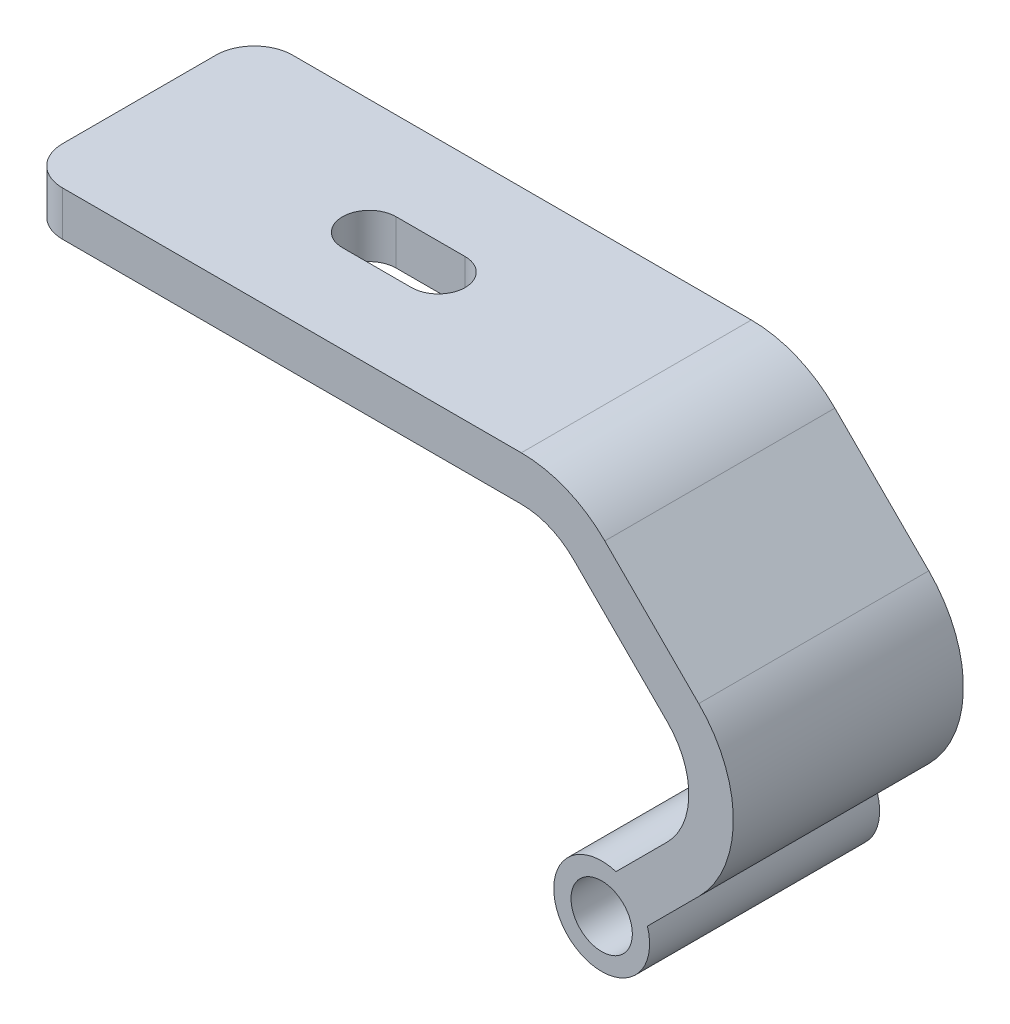
SolidWorks part; units mm, degrees
ref_plane "Front Plane" through (0, 0, 0) normal (0, 0, 1) x (1, 0, 0)
ref_plane "Top Plane" through (0, 0, 0) normal (0, 1, 0) x (1, 0, 0)
ref_plane "Right Plane" through (0, 0, 0) normal (1, 0, 0) x (0, 0, -1)
sketch "Sketch1" plane through (0, 0, 0) normal (0, 0, 1) x (1, 0, 0)
  line L0 (-32.4112, 0) -> (32.4112, 0) construction
  line L1 (41.25, -3.6612) -> (53.4987, -15.9099) construction
  line L2 (53.4987, -33.5876) -> (42.8921, -44.1942) construction
  line L3 (-32.4112, -2.9) -> (32.4112, -2.9)
  line L4 (39.1994, -5.7118) -> (51.4481, -17.9605)
  line L5 (51.4481, -31.537) -> (44.7564, -38.2287)
  line L6 (-32.4112, 2.9) -> (32.4112, 2.9)
  line L7 (43.3006, -1.6106) -> (55.5493, -13.8593)
  line L8 (55.5493, -35.6382) -> (48.8576, -42.3299)
  line L9 (-32.4112, -2.9) -> (-32.4112, 2.9)
  line L10 (55.5493, -35.6382) -> (44.9427, -46.2448) construction
  line L11 (51.4481, -31.537) -> (40.8415, -42.1436) construction
  arc A0 (53.4987, -15.9099) -> (53.4987, -33.5876) centre (44.6599, -24.7487) cw construction
  arc A1 (32.4112, 0) -> (41.25, -3.6612) centre (32.4112, -12.5) cw construction
  arc A2 (32.4112, -2.9) -> (39.1994, -5.7118) centre (32.4112, -12.5) cw
  arc A3 (51.4481, -17.9605) -> (51.4481, -31.537) centre (44.6599, -24.7487) cw
  arc A4 (32.4112, 2.9) -> (43.3006, -1.6106) centre (32.4112, -12.5) cw
  arc A5 (55.5493, -13.8593) -> (55.5493, -35.6382) centre (44.6599, -24.7487) cw
  circle A6 centre (42.8921, -44.1942) radius 4
  arc A7 (44.7564, -38.2287) -> (48.8576, -42.3299) centre (42.8921, -44.1942) ccw
  point P4 (0, 0)
  point P8 (62.3376, -24.7487)
  point P11 (37.5888, 0)
  dimension "D6" = 12.5
  dimension "D9" = 8
  dimension "D10" = 12.5
  dimension "D1" = 70
  dimension "D2" = 35
  dimension "D3" = 27.5
  dimension "D4" = 135
  dimension "D5" = 270
  dimension "D7" = 2.9
  dimension "D8" = 2.9
extrude "Boss-Extrude1" add sketch "Sketch1" along normal mid plane 30
sketch "Sketch2" plane through (0, 2.9, 0) normal (0, 1, 0) x (1, 0, 0)
  line L0 (-2.4112, 0) -> (6.5888, 0) construction
  line L1 (-2.4112, 3.5) -> (6.5888, 3.5)
  line L2 (-2.4112, -3.5) -> (6.5888, -3.5)
  line L3 (-32.4112, -15) -> (-32.4112, 15) construction
  arc A0 (-2.4112, 3.5) -> (-2.4112, -3.5) centre (-2.4112, 0) ccw
  arc A1 (6.5888, -3.5) -> (6.5888, 3.5) centre (6.5888, 0) ccw
  point P3 (2.0888, 0)
  dimension "D1" = 30
  dimension "D2" = 9
  dimension "D3" = 7
extrude "Cut-Extrude1" cut sketch "Sketch2" against normal up to next
fillet "Fillet1" radius 5 2 edges at (-32.4112, 0, -15) (-32.4112, 0, 15)
